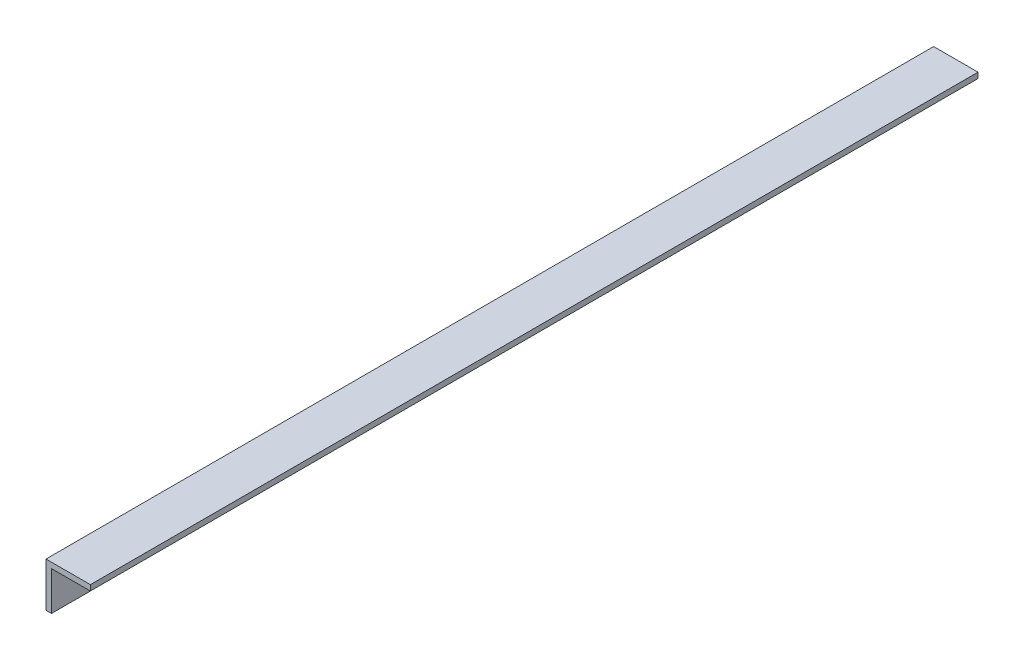
SolidWorks part; units mm, degrees
ref_plane "Front Plane" through (0, 0, 0) normal (0, 0, 1) x (1, 0, 0)
ref_plane "Top Plane" through (0, 0, 0) normal (0, 1, 0) x (1, 0, 0)
ref_plane "Right Plane" through (0, 0, 0) normal (1, 0, 0) x (0, 0, -1)
sketch "Sketch1" plane through (0, 0, 0) normal (0, 0, 1) x (1, 0, 0)
  line L0 (0, 0) -> (0, 25.4)
  line L1 (0, 25.4) -> (25.4, 25.4)
  line L2 (25.4, 25.4) -> (25.4, 22.225)
  line L3 (25.4, 22.225) -> (3.175, 22.225)
  line L4 (3.175, 22.225) -> (3.175, 0)
  line L5 (3.175, 0) -> (0, 0)
  dimension "D1" = 3.175
  dimension "D2" = 3.175
  dimension "D3" = 25.4
  dimension "D4" = 25.4
extrude "Boss-Extrude1" add sketch "Sketch1" along normal blind 508
